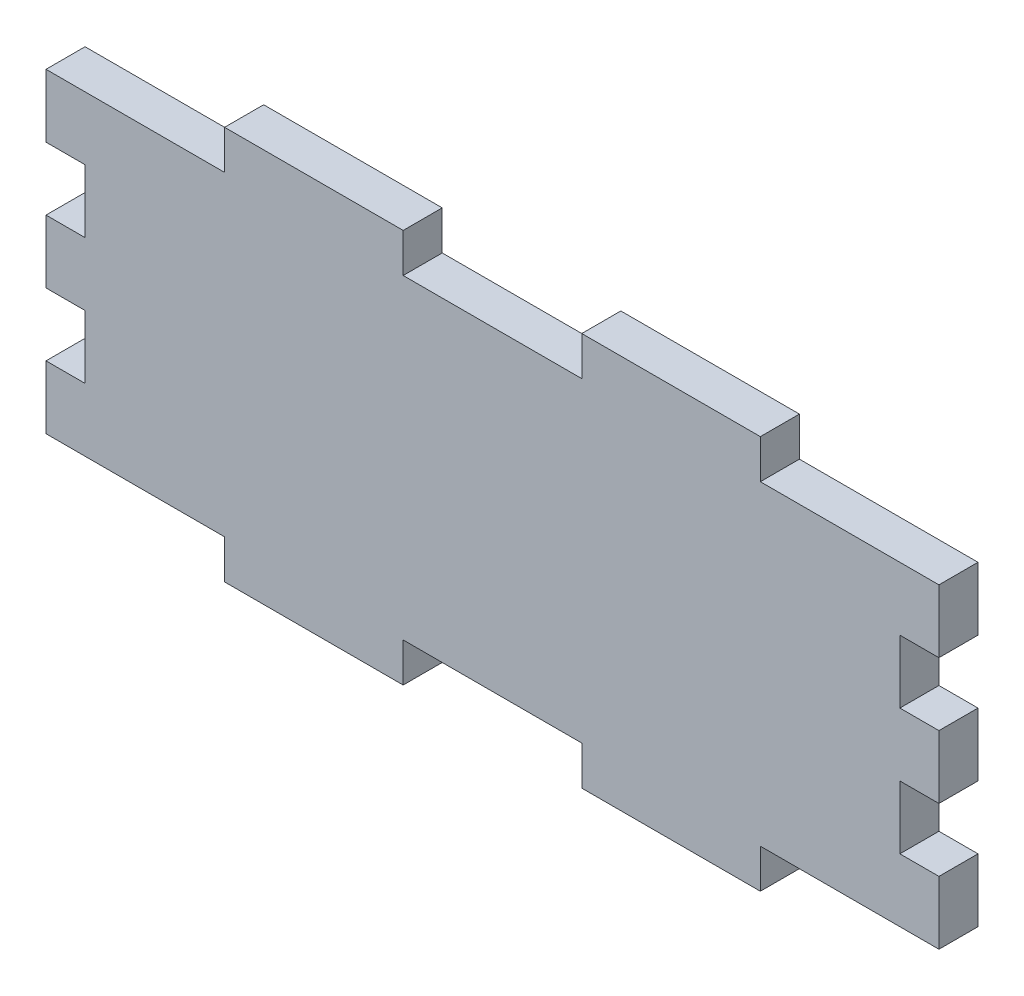
SolidWorks part; units mm, degrees
ref_plane "Front Plane" through (0, 0, 0) normal (0, 0, 1) x (1, 0, 0)
ref_plane "Top Plane" through (0, 0, 0) normal (0, 1, 0) x (1, 0, 0)
ref_plane "Right Plane" through (0, 0, 0) normal (1, 0, 0) x (0, 0, -1)
ref_plane "Plane1" through (183.8691, 68.2878, 10) normal (-1, 0, 0) x (0, 0, 1)
sketch "Sketch3" plane through (0, 0, 0) normal (0, 0, 1) x (1, 0, 0)
  line L4 (148.1491, 78.2878) -> (102.4291, 78.2878)
  line L12 (183.8691, 68.2878) -> (148.1491, 68.2878)
  line L18 (-34.7309, 78.2878) -> (-34.7309, -22.5122) construction
  line L24 (102.4291, 78.2878) -> (102.4291, 68.2878)
  line L25 (148.1491, 78.2878) -> (148.1491, 68.2878)
  line L26 (-34.7309, 35.9678) -> (-34.7309, 19.8078)
  line L27 (79.5691, 68.2878) -> (79.5691, 55.5878) construction
  line L29 (183.8691, 68.2878) -> (-24.7309, 68.2878) construction
  line L30 (102.4291, 68.2878) -> (56.7091, 68.2878)
  line L31 (193.8691, 78.2878) -> (-34.7309, 78.2878) construction
  line L33 (-34.7309, 68.2878) -> (-34.7309, 52.1278)
  line L34 (183.8691, 68.2878) -> (193.8691, 68.2878)
  line L35 (193.8691, 78.2878) -> (193.8691, -22.5122) construction
  line L36 (-24.7309, 68.2878) -> (-24.7309, -12.5122) construction
  line L37 (183.8691, -12.5122) -> (-24.7309, -12.5122) construction
  line L38 (193.8691, -22.5122) -> (-34.7309, -22.5122) construction
  line L39 (183.8691, 68.2878) -> (183.8691, -12.5122) construction
  line L40 (183.8691, 52.1278) -> (183.8691, 35.9678)
  line L41 (183.8691, 52.1278) -> (193.8691, 52.1278)
  line L42 (183.8691, 35.9678) -> (193.8691, 35.9678)
  line L43 (183.8691, 27.8878) -> (193.8691, 27.8878) construction
  line L44 (193.8691, 68.2878) -> (193.8691, 52.1278)
  line L45 (183.8691, 19.8078) -> (193.8691, 19.8078) [skipped]
  line L46 (183.8691, 3.6478) -> (193.8691, 3.6478) [skipped]
  line L47 (193.8691, 35.9678) -> (193.8691, 19.8078)
  line L48 (-24.7309, 27.8878) -> (-34.7309, 27.8878) construction
  line L49 (-24.7309, 35.9678) -> (-34.7309, 35.9678)
  line L50 (-24.7309, 52.1278) -> (-34.7309, 52.1278)
  line L51 (-24.7309, 52.1278) -> (-24.7309, 35.9678)
  line L52 (-24.7309, 68.2878) -> (-34.7309, 68.2878)
  line L53 (10.9891, 78.2878) -> (10.9891, 68.2878)
  line L54 (56.7091, 78.2878) -> (56.7091, 68.2878)
  line L55 (-24.7309, 68.2878) -> (10.9891, 68.2878)
  line L56 (10.9891, 78.2878) -> (56.7091, 78.2878)
  line L57 (148.1491, 78.2878) -> (102.4291, 78.2878)
  line L58 (183.8691, 68.2878) -> (148.1491, 68.2878)
  line L59 (102.4291, 78.2878) -> (102.4291, 68.2878)
  line L60 (148.1491, 78.2878) -> (148.1491, 68.2878)
  line L61 (183.8691, 68.2878) -> (193.8691, 68.2878)
  line L62 (183.8691, 52.1278) -> (183.8691, 35.9678)
  line L63 (183.8691, 52.1278) -> (193.8691, 52.1278)
  line L64 (183.8691, 35.9678) -> (193.8691, 35.9678)
  line L65 (183.8691, 27.8878) -> (193.8691, 27.8878) construction
  line L66 (-34.7309, 35.9678) -> (-34.7309, 19.8078)
  line L67 (-34.7309, 68.2878) -> (-34.7309, 52.1278)
  line L68 (-24.7309, 27.8878) -> (-34.7309, 27.8878) construction
  line L69 (-24.7309, 35.9678) -> (-34.7309, 35.9678)
  line L70 (-24.7309, 52.1278) -> (-34.7309, 52.1278)
  line L71 (-24.7309, 52.1278) -> (-24.7309, 35.9678)
  line L72 (-24.7309, 68.2878) -> (-34.7309, 68.2878)
  line L73 (193.8691, 68.2878) -> (193.8691, 52.1278)
  line L74 (193.8691, 35.9678) -> (193.8691, 19.8078)
  line L75 (10.9891, 78.2878) -> (10.9891, 68.2878)
  line L76 (56.7091, 78.2878) -> (56.7091, 68.2878)
  line L77 (-24.7309, 68.2878) -> (10.9891, 68.2878)
  line L78 (10.9891, 78.2878) -> (56.7091, 78.2878)
  line L79 (79.5691, -12.5122) -> (79.5691, 0.1878) construction
  line L80 (10.9891, -22.5122) -> (56.7091, -22.5122)
  line L81 (-24.7309, -12.5122) -> (10.9891, -12.5122)
  line L82 (56.7091, -22.5122) -> (56.7091, -12.5122)
  line L83 (10.9891, -22.5122) -> (10.9891, -12.5122)
  line L84 (193.8691, -12.5122) -> (193.8691, 3.6478)
  line L85 (-24.7309, -12.5122) -> (-34.7309, -12.5122)
  line L86 (-24.7309, 3.6478) -> (-24.7309, 19.8078)
  line L87 (-24.7309, 3.6478) -> (-34.7309, 3.6478)
  line L88 (-24.7309, 19.8078) -> (-34.7309, 19.8078)
  line L89 (-34.7309, -12.5122) -> (-34.7309, 3.6478)
  line L90 (183.8691, 19.8078) -> (193.8691, 19.8078)
  line L91 (183.8691, 3.6478) -> (193.8691, 3.6478)
  line L92 (183.8691, 3.6478) -> (183.8691, 19.8078)
  line L93 (183.8691, -12.5122) -> (193.8691, -12.5122)
  line L94 (148.1491, -22.5122) -> (148.1491, -12.5122)
  line L95 (102.4291, -22.5122) -> (102.4291, -12.5122)
  line L96 (183.8691, -12.5122) -> (148.1491, -12.5122)
  line L97 (148.1491, -22.5122) -> (102.4291, -22.5122)
  line L98 (10.9891, -22.5122) -> (56.7091, -22.5122)
  line L99 (-24.7309, -12.5122) -> (10.9891, -12.5122)
  line L100 (56.7091, -22.5122) -> (56.7091, -12.5122)
  line L101 (10.9891, -22.5122) -> (10.9891, -12.5122)
  line L102 (-24.7309, -12.5122) -> (-34.7309, -12.5122)
  line L103 (-24.7309, 3.6478) -> (-24.7309, 19.8078)
  line L104 (-24.7309, 3.6478) -> (-34.7309, 3.6478)
  line L105 (-24.7309, 19.8078) -> (-34.7309, 19.8078)
  line L106 (193.8691, -12.5122) -> (193.8691, 3.6478)
  line L107 (183.8691, 19.8078) -> (193.8691, 19.8078)
  line L108 (183.8691, 3.6478) -> (193.8691, 3.6478)
  line L109 (183.8691, 3.6478) -> (183.8691, 19.8078)
  line L110 (183.8691, -12.5122) -> (193.8691, -12.5122)
  line L111 (-34.7309, -12.5122) -> (-34.7309, 3.6478)
  line L112 (102.4291, -12.5122) -> (56.7091, -12.5122)
  line L113 (148.1491, -22.5122) -> (148.1491, -12.5122)
  line L114 (102.4291, -22.5122) -> (102.4291, -12.5122)
  line L115 (183.8691, -12.5122) -> (148.1491, -12.5122)
  line L116 (148.1491, -22.5122) -> (102.4291, -22.5122)
  circle A1 centre (171.1691, 55.5878) radius 4
  circle A5 centre (-12.0309, 55.5878) radius 4
  circle A6 centre (171.1691, 55.5878) radius 4
  circle A7 centre (-12.0309, 55.5878) radius 4
  circle A8 centre (-12.0309, 0.1878) radius 4
  circle A9 centre (171.1691, 0.1878) radius 4
  circle A10 centre (-12.0309, 0.1878) radius 4
  circle A11 centre (171.1691, 0.1878) radius 4
  point P10 (79.5691, 27.8878)
  dimension "D1" = 5
  dimension "D5" = 10
extrude "Boss-Extrude2" add sketch "Sketch3" along normal blind 10 contours L112 L95 L97 L94 L96 L93 L84 L91 L92 L90 L47 L42 L40 L41 L44 L34 L12 L25 L4 L24 L30 L54 L56 L53 L55 L52 L33 L50 L51 L49 L26 L88 L86 L87 L89 L85 L81 L83 L80 L82 A5 A1 A8 A9 | A5 | A8 | A9 | A1
